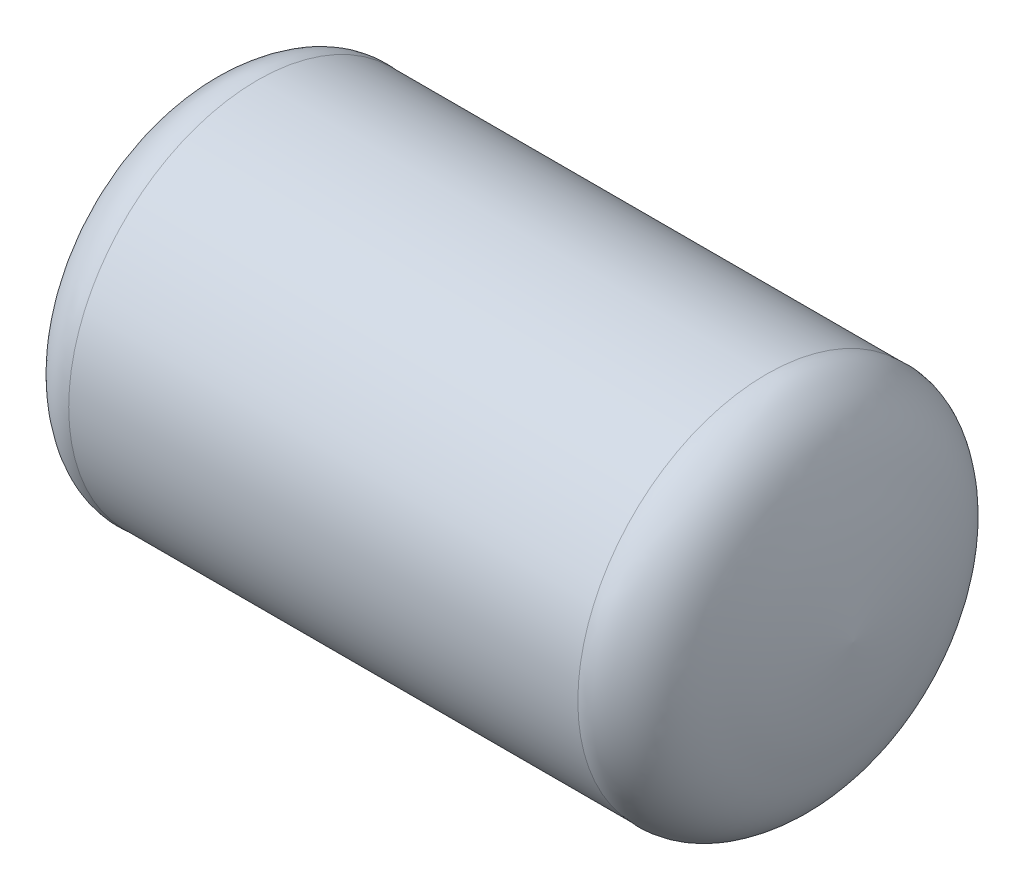
SolidWorks part; units mm, degrees
ref_plane "前视基准面" through (0, 0, 0) normal (0, 0, 1) x (1, 0, 0)
ref_plane "上视基准面" through (0, 0, 0) normal (0, 1, 0) x (1, 0, 0)
ref_plane "右视基准面" through (0, 0, 0) normal (1, 0, 0) x (0, 0, -1)
sketch "草图1" plane through (0, 0, 0) normal (0, 0, 1) x (1, 0, 0)
  line L0 (0, 0) -> (129.0873, 0) construction
  line L1 (-96.3097, 71.4229) -> (96.3097, 71.4229)
  line L2 (0, 0) -> (0, 95.3253) construction
  line L3 (-129.0873, 0) -> (129.0873, 0)
  spline S0 degree 3 poles (129.0873, 0) (128.3538, 9.7814) (126.3287, 27.1874) (120.3277, 49.6485) (115.9504, 64.646) (100.9066, 72.1516) (96.3097, 71.4229) knots 0 0 0 0 0.38235 0.474548 0.872268 1 1 1 1
  spline S1 degree 3 poles (-129.0873, 0) (-128.3538, 9.7814) (-126.3287, 27.1874) (-120.3277, 49.6485) (-115.9504, 64.646) (-100.9066, 72.1516) (-96.3097, 71.4229) knots 0 0 0 0 0.38235 0.474548 0.872268 1 1 1 1
  point P12 (0, 71.4229)
revolve "旋转1" add sketch "草图1" angle 360 about L3
sketch "草图4" plane through (0, 0, 0) normal (0, 0, 1) x (1, 0, 0)
  line L5 (-126.0788, 0) -> (126.0788, 0)
  line L7 (-96.546, -68.4229) -> (96.546, -68.4229)
  line L8 (96.546, 68.4229) -> (-96.546, 68.4229)
  line L10 (96.546, 68.4229) -> (-96.546, 68.4229)
  spline S20 degree 3 poles (64.6618, -1067.8683) (76.6533, -45.3337) (86.8985, -67.2881) (97.389, -68.5405) (97.5998, -68.5591) (98.2322, -68.5944) (98.6538, -68.5908) (99.4971, -68.5271) (99.9215, -68.4664) (100.7574, -68.291) (101.1661, -68.1774) (101.9677, -67.9057) (102.3606, -67.7476) (103.133, -67.3938) (103.5138, -67.1973) (104.6246, -66.5705) (105.3271, -66.1022) (106.69, -65.1104) (107.3487, -64.5844) (108.3002, -63.7473) (108.6113, -63.4602) (109.2211, -62.8696) (109.5199, -62.5657) (110.9692, -61.0186) (111.9946, -59.6824) (113.359, -57.5503) (113.7861, -56.8166) (114.5847, -55.32) (114.9536, -54.5626) (115.9878, -52.2682) (116.5808, -50.7094) (117.6542, -47.5579) (118.1345, -45.9651) (118.8191, -43.565) (119.0412, -42.7631) (119.4805, -41.1579) (119.6985, -40.3548) (120.3454, -37.9433) (120.7636, -36.3317) (121.5324, -33.0881) (121.8813, -31.4555) (122.5268, -28.1745) (122.8238, -26.5271) (123.3778, -23.2299) (123.6349, -21.5788) (124.3578, -16.6192) (124.7762, -13.3048) (139.2189, 117.499) (78.6477, 254.4699) (-746.4174, 488.6121) knots -0.373226 -0.373226 -0.373226 -0.373226 0.007812 0.007812 0.015625 0.015625 0.03125 0.03125 0.046875 0.046875 0.0625 0.0625 0.078125 0.078125 0.09375 0.09375 0.125 0.125 0.15625 0.15625 0.171875 0.171875 0.1875 0.1875 0.25 0.25 0.28125 0.28125 0.3125 0.3125 0.375 0.375 0.4375 0.4375 0.46875 0.46875 0.5 0.5 0.5625 0.5625 0.625 0.625 0.6875 0.6875 0.75 0.75 0.875 0.875 5.673371 5.673371 5.673371 5.673371 only from (96.546, -68.4229) to (126.0788, 0)
  spline S21 degree 3 poles (-3661.0207, -1179.3541) (-35.7505, -445.6104) (148.6633, -202.9691) (124.7747, 13.3179) (124.3558, 16.6341) (123.3913, 23.2485) (122.8474, 26.5469) (121.8777, 31.4725) (121.5276, 33.1106) (120.7526, 36.376) (120.3308, 37.9992) (119.6789, 40.4274) (119.4593, 41.2362) (119.0166, 42.8526) (118.7925, 43.66) (118.1016, 46.0764) (117.6161, 47.6798) (116.8006, 50.0585) (116.5141, 50.8469) (115.9021, 52.4119) (115.5757, 53.1902) (114.5285, 55.4878) (113.7409, 56.9669) (112.3766, 59.0779) (111.8914, 59.7636) (110.8527, 61.0948) (110.3029, 61.735) (108.5776, 63.56) (107.3193, 64.6567) (105.2805, 66.1338) (104.5725, 66.6027) (103.1046, 67.4252) (102.344, 67.7801) (101.1425, 68.1844) (100.7314, 68.2973) (99.9079, 68.4684) (99.4931, 68.5274) (98.6568, 68.5906) (98.2351, 68.5946) (97.5983, 68.559) (97.3869, 68.5403) (80.9575, 66.5755) (70.6116, 13.9907) (-412.0425, 4034.4452) knots -7.884467 -7.884467 -7.884467 -7.884467 0.125 0.125 0.25 0.25 0.375 0.375 0.4375 0.4375 0.5 0.5 0.53125 0.53125 0.5625 0.5625 0.625 0.625 0.65625 0.65625 0.6875 0.6875 0.75 0.75 0.78125 0.78125 0.8125 0.8125 0.875 0.875 0.90625 0.90625 0.9375 0.9375 0.953125 0.953125 0.96875 0.96875 0.984375 0.984375 0.992188 0.992188 1.593529 1.593529 1.593529 1.593529 only from (126.0788, 0) to (96.546, 68.4229)
  spline S22 degree 3 poles (739.7289, 500.3694) (-79.2734, 254.5013) (-139.1658, 116.9786) (-124.7747, -13.3179) (-124.3558, -16.6341) (-123.3913, -23.2485) (-122.8474, -26.5469) (-121.8777, -31.4725) (-121.5276, -33.1106) (-120.7526, -36.376) (-120.3308, -37.9992) (-119.6789, -40.4274) (-119.4593, -41.2362) (-119.0166, -42.8526) (-118.7925, -43.66) (-118.1016, -46.0764) (-117.6161, -47.6798) (-116.8006, -50.0585) (-116.5141, -50.8469) (-115.9021, -52.4119) (-115.5757, -53.1902) (-114.5285, -55.4878) (-113.7409, -56.9669) (-112.3766, -59.0779) (-111.8914, -59.7636) (-110.8527, -61.0948) (-110.3029, -61.735) (-108.5776, -63.56) (-107.3193, -64.6567) (-105.2805, -66.1338) (-104.5725, -66.6027) (-103.1046, -67.4252) (-102.344, -67.7801) (-101.1425, -68.1844) (-100.7314, -68.2973) (-99.9079, -68.4684) (-99.4931, -68.5274) (-98.6568, -68.5906) (-98.2351, -68.5946) (-97.5983, -68.559) (-97.3869, -68.5403) (-86.8836, -67.2842) (-78.9561, -45.6566) (48.8211, -1057.5763) knots -4.650399 -4.650399 -4.650399 -4.650399 0.125 0.125 0.25 0.25 0.375 0.375 0.4375 0.4375 0.5 0.5 0.53125 0.53125 0.5625 0.5625 0.625 0.625 0.65625 0.65625 0.6875 0.6875 0.75 0.75 0.78125 0.78125 0.8125 0.8125 0.875 0.875 0.90625 0.90625 0.9375 0.9375 0.953125 0.953125 0.96875 0.96875 0.984375 0.984375 0.992188 0.992188 1.373808 1.373808 1.373808 1.373808 only from (-126.0788, 0) to (-96.546, -68.4229)
  spline S23 degree 3 poles (-41.9252, 4066.793) (-64.892, 13.2636) (-80.9922, 66.583) (-97.389, 68.5405) (-97.5998, 68.5591) (-98.2322, 68.5944) (-98.6538, 68.5908) (-99.4971, 68.5271) (-99.9215, 68.4664) (-100.7574, 68.291) (-101.1661, 68.1774) (-101.9677, 67.9057) (-102.3606, 67.7476) (-103.133, 67.3938) (-103.5138, 67.1973) (-104.6246, 66.5705) (-105.3271, 66.1022) (-106.69, 65.1104) (-107.3487, 64.5844) (-108.3002, 63.7473) (-108.6113, 63.4602) (-109.2211, 62.8696) (-109.5199, 62.5657) (-110.9692, 61.0186) (-111.9946, 59.6824) (-113.359, 57.5503) (-113.7861, 56.8166) (-114.5847, 55.32) (-114.9536, 54.5626) (-115.9878, 52.2682) (-116.5808, 50.7094) (-117.6542, 47.5579) (-118.1345, 45.9651) (-118.8191, 43.565) (-119.0412, 42.7631) (-119.4805, 41.1579) (-119.6985, 40.3548) (-120.3454, 37.9433) (-120.7636, 36.3317) (-121.5324, 33.0881) (-121.8813, 31.4555) (-122.5268, 28.1745) (-122.8238, 26.5271) (-123.3778, 23.2299) (-123.6349, 21.5788) (-124.3578, 16.6192) (-124.7762, 13.3048) (-148.7274, -203.6156) (37.249, -443.8514) (3677.6611, -1123.1646) knots -0.592153 -0.592153 -0.592153 -0.592153 0.007813 0.007813 0.015625 0.015625 0.03125 0.03125 0.046875 0.046875 0.0625 0.0625 0.078125 0.078125 0.09375 0.09375 0.125 0.125 0.15625 0.15625 0.171875 0.171875 0.1875 0.1875 0.25 0.25 0.28125 0.28125 0.3125 0.3125 0.375 0.375 0.4375 0.4375 0.46875 0.46875 0.5 0.5 0.5625 0.5625 0.625 0.625 0.6875 0.6875 0.75 0.75 0.875 0.875 8.914745 8.914745 8.914745 8.914745 only from (-96.546, 68.4229) to (-126.0788, 0)
  spline S25 degree 3 poles (126.0788, 0) (125.8253, 3.3398) (125.5088, 6.6707) (124.7747, 13.3179) (124.3558, 16.6341) (123.3913, 23.2485) (122.8474, 26.5469) (121.8777, 31.4725) (121.5276, 33.1106) (120.7526, 36.376) (120.3308, 37.9992) (119.6789, 40.4274) (119.4593, 41.2362) (119.0166, 42.8526) (118.7925, 43.66) (118.1016, 46.0764) (117.6161, 47.6798) (116.8006, 50.0585) (116.5141, 50.8469) (115.9021, 52.4119) (115.5757, 53.1902) (114.5285, 55.4878) (113.7409, 56.9669) (112.3766, 59.0779) (111.8914, 59.7636) (110.8527, 61.0948) (110.3029, 61.735) (108.5776, 63.56) (107.3193, 64.6567) (105.2805, 66.1338) (104.5725, 66.6027) (103.1046, 67.4252) (102.344, 67.7801) (101.1425, 68.1844) (100.7314, 68.2973) (99.9079, 68.4684) (99.4931, 68.5274) (98.6568, 68.5906) (98.2351, 68.5946) (97.5983, 68.559) (97.3869, 68.5403) (96.9655, 68.4899) (96.7557, 68.4562) (96.546, 68.4229) knots 0 0 0 0 0.125 0.125 0.25 0.25 0.375 0.375 0.4375 0.4375 0.5 0.5 0.53125 0.53125 0.5625 0.5625 0.625 0.625 0.65625 0.65625 0.6875 0.6875 0.75 0.75 0.78125 0.78125 0.8125 0.8125 0.875 0.875 0.90625 0.90625 0.9375 0.9375 0.953125 0.953125 0.96875 0.96875 0.984375 0.984375 0.992188 0.992188 1 1 1 1
  spline S27 degree 3 poles (-96.546, 68.4229) (-96.7567, 68.4563) (-96.9675, 68.4902) (-97.389, 68.5405) (-97.5998, 68.5591) (-98.2322, 68.5944) (-98.6538, 68.5908) (-99.4971, 68.5271) (-99.9215, 68.4664) (-100.7574, 68.291) (-101.1661, 68.1774) (-101.9677, 67.9057) (-102.3606, 67.7476) (-103.133, 67.3938) (-103.5138, 67.1973) (-104.6246, 66.5705) (-105.3271, 66.1022) (-106.69, 65.1104) (-107.3487, 64.5844) (-108.3002, 63.7473) (-108.6113, 63.4602) (-109.2211, 62.8696) (-109.5199, 62.5657) (-110.9692, 61.0186) (-111.9946, 59.6824) (-113.359, 57.5503) (-113.7861, 56.8166) (-114.5847, 55.32) (-114.9536, 54.5626) (-115.9878, 52.2682) (-116.5808, 50.7094) (-117.6542, 47.5579) (-118.1345, 45.9651) (-118.8191, 43.565) (-119.0412, 42.7631) (-119.4805, 41.1579) (-119.6985, 40.3548) (-120.3454, 37.9433) (-120.7636, 36.3317) (-121.5324, 33.0881) (-121.8813, 31.4555) (-122.5268, 28.1745) (-122.8238, 26.5271) (-123.3778, 23.2299) (-123.6349, 21.5788) (-124.3578, 16.6192) (-124.7762, 13.3048) (-125.5096, 6.6629) (-125.8256, 3.3354) (-126.0788, 0) knots 0 0 0 0 0.007813 0.007813 0.015625 0.015625 0.03125 0.03125 0.046875 0.046875 0.0625 0.0625 0.078125 0.078125 0.09375 0.09375 0.125 0.125 0.15625 0.15625 0.171875 0.171875 0.1875 0.1875 0.25 0.25 0.28125 0.28125 0.3125 0.3125 0.375 0.375 0.4375 0.4375 0.46875 0.46875 0.5 0.5 0.5625 0.5625 0.625 0.625 0.6875 0.6875 0.75 0.75 0.875 0.875 1 1 1 1
  dimension "D1" = 3
revolve "切除-旋转1" cut sketch "草图4" angle 360 about L5
